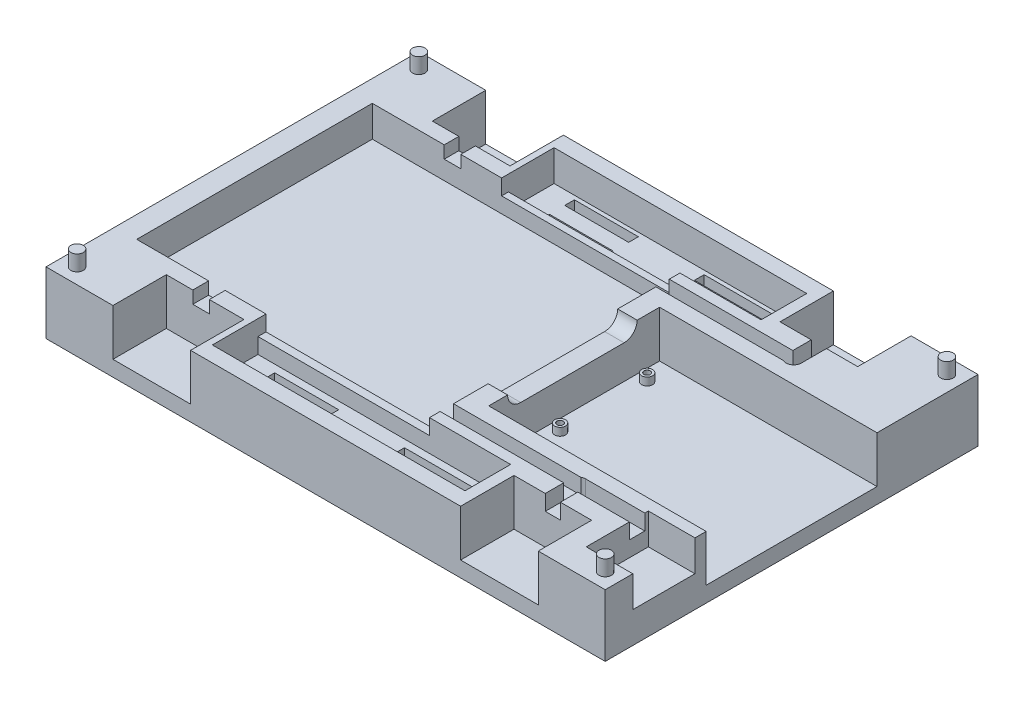
SolidWorks part; units mm, degrees
ref_plane "Front Plane" through (0, 0, 0) normal (0, 0, 1) x (1, 0, 0)
ref_plane "Top Plane" through (0, 0, 0) normal (0, 1, 0) x (1, 0, 0)
ref_plane "Right Plane" through (0, 0, 0) normal (1, 0, 0) x (0, 0, -1)
sketch "Sketch1" plane through (0, 0, 0) normal (0, 1, 0) x (1, 0, 0)
  line L1 (90, 60) -> (-90, 60)
  line L2 (90, 60) -> (90, -60)
  line L3 (90, -60) -> (-90, -60)
  line L4 (-90, 60) -> (-90, -60)
  line L5 (90, 60) -> (-90, -60) construction
  line L6 (90, -60) -> (-90, 60) construction
  point P0 (0, 0)
  dimension "D1" = 180
  dimension "D2" = 120
extrude "Boss-Extrude1" add sketch "Sketch1" along normal blind 20
sketch "Sketch2" plane through (0, 20, 0) normal (0, 1, 0) x (1, 0, 0)
  line L0 (90, 0) -> (90, 27.5)
  line L1 (90, -60) -> (90, 60) construction
  line L2 (90, 0) -> (90, -27.5)
  line L3 (90, 27.5) -> (20, 27.5)
  line L4 (20, 27.5) -> (20, -27.5)
  line L5 (20, -27.5) -> (90, -27.5)
  dimension "D1" = 27.5
  dimension "D2" = 27.5
  dimension "D3" = 70
extrude "Cut-Extrude1" cut sketch "Sketch2" against normal blind 15
sketch "Sketch3" plane through (0, 20, 0) normal (0, 1, 0) x (1, 0, 0)
  line L0 (-90, -60) -> (90, -60) construction
  line L1 (68.4559, -77.185) -> (43.4559, -77.185)
  line L2 (68.4559, -77.185) -> (68.4559, -42.815)
  line L3 (68.4559, -42.815) -> (43.4559, -42.815)
  line L4 (43.4559, -77.185) -> (43.4559, -42.815)
  line L5 (68.4559, -77.185) -> (43.4559, -42.815) construction
  line L6 (68.4559, -42.815) -> (43.4559, -77.185) construction
  point P0 (55.9559, -60)
  dimension "D1" = 25
  dimension "D2" = 34.37
extrude "Cut-Extrude2" cut sketch "Sketch3" against normal blind 15
mirror "Mirror1" about plane through (0, 0, 0) normal (1, 0, 0) of "Cut-Extrude2"
mirror "Mirror2" about plane through (0, 0, 0) normal (0, 0, 1) of "Mirror1", "Cut-Extrude2"
sketch "Sketch4" plane through (0, 20, 0) normal (0, 1, 0) x (1, 0, 0)
  line L1 (-83.0687, 38.109) -> (13.7398, 38.109)
  line L2 (-83.0687, 38.109) -> (-83.0687, -37.7325)
  line L3 (-83.0687, -37.7325) -> (13.7398, -37.7325)
  line L4 (13.7398, 38.109) -> (13.7398, -37.7325)
  dimension "D1" = 75.8415
  dimension "D2" = 96.8085
extrude "Cut-Extrude4" cut sketch "Sketch4" against normal blind 10
sketch "Sketch6" plane through (0, 5, 0) normal (0, 1, 0) x (1, 0, 0)
  line L0 (-62.6949, -357.8384) -> (-777.3616, -357.8384) construction
  circle A0 centre (23.7402, 19.7599) radius 1.7503
  circle A1 centre (23.7402, -8.258) radius 1.75
  circle A3 centre (74.9588, -23.6924) radius 1.75
  dimension "D1" = 3.5
  dimension "D2" = 3.5007
  dimension "D4" = 3.5
extrude "Boss-Extrude2" add sketch "Sketch6" along normal blind 2.5
hole_wizard "Ø2.0 (2) Diameter Hole1" positions "3DSketch7" profile "Sketch12" hole size "Ø2.0" standard "AS"
sketch3d "3DSketch7"
  line L0 (23.7402, 7.5, -19.7599) -> (23.7402, 5, -19.7599) construction
  line L1 (23.7402, 7.5, 8.258) -> (23.7402, 5, 8.258) construction
  line L2 (74.9588, 7.5, 23.6924) -> (74.9588, 5, 23.6924) construction
  point P0 (23.7402, 7.5, -19.7599)
  point P4 (23.7402, 7.5, 8.258)
  point P8 (74.9588, 7.5, 23.6924)
sketch "Sketch12" plane through (23.7402, 7.5, -19.7599) normal (1, 0, 0) x (0, 0, 1)
  line L0 (0, 0) -> (0, 2.6009)
  line L1 (0, 2.6009) -> (1, 2)
  line L2 (1, 2) -> (1, 0.0241)
  line L3 (1, 0.0241) -> (1.025, 0)
  line L5 (1.025, 0) -> (0, 0)
  line L6 (-1, 0.0241) -> (-1.025, 0) construction
  line L10 (0, 2.6009) -> (-1, 2) construction
  line L11 (0, -6.35) -> (0, 107.95) construction
  dimension "Hole Dia." = 2
  dimension "Hole Depth" = 2
  dimension "Near C'Sink Dia." = 2.05
  dimension "Near C'Sink Angle" = 92
  dimension "Drill Angle" = 118
sketch "Sketch14" plane through (0, 20, 0) normal (0, 1, 0) x (1, 0, 0)
  line L0 (-90, 60) -> (-90, 55)
  line L1 (-90, 60) -> (-90, -60) construction
  line L2 (-90, 55) -> (-85, 55)
  line L3 (90, 60) -> (90, 55)
  line L4 (90, 27.5) -> (90, 60) construction
  line L5 (90, 55) -> (85, 55)
  line L6 (-90, -60) -> (-90, -55)
  line L7 (-90, -55) -> (-85, -55)
  line L8 (90, -60) -> (90, -55)
  line L9 (90, -60) -> (90, -27.5) construction
  line L10 (90, -55) -> (85, -55)
  dimension "D1" = 5
  dimension "D2" = 5
  dimension "D3" = 5
  dimension "D4" = 5
  dimension "D5" = 5
  dimension "D6" = 5
  dimension "D7" = 5
  dimension "D8" = 5
sketch "Sketch19" plane through (20, 0, 0) normal (1, 0, 0) x (0, 0, -1)
  line L0 (-17.2052, 20) -> (16.0767, 20) construction
  line L1 (27.5, 20) -> (-27.5, 20) construction
  line L2 (-17.2052, 24.2066) -> (16.0767, 24.2066)
  line L3 (-17.2052, 15.7934) -> (16.0767, 15.7934)
  arc A0 (-17.2052, 24.2066) -> (-17.2052, 15.7934) centre (-17.2052, 20) ccw
  arc A1 (16.0767, 15.7934) -> (16.0767, 24.2066) centre (16.0767, 20) ccw
  point P4 (-0.5642, 20)
extrude "Cut-Extrude5" cut sketch "Sketch19" against normal blind 10
sketch "Sketch21" plane through (0, 0, 60) normal (0, 0, 1) x (1, 0, 0)
  line L0 (-43.4559, 20) -> (43.4559, 20) construction
  line L1 (-4.863, 20) -> (-16.863, 20)
  line L2 (-4.863, 20) -> (-4.863, 14)
  line L3 (-4.863, 14) -> (-16.863, 14)
  line L4 (-16.863, 20) -> (-16.863, 14)
  dimension "D1" = 6
  dimension "D2" = 12
sketch "Sketch22" plane through (0, 0, 37.7325) normal (0, 0, -1) x (-1, 0, 0)
  line L0 (83.0687, 20) -> (-13.7398, 20) construction
  line L1 (12.735, 20) -> (8.1365, 20)
  line L2 (12.735, 20) -> (12.735, 18.4462)
  line L3 (12.735, 18.4462) -> (8.1365, 18.4462)
  line L4 (8.1365, 20) -> (8.1365, 18.4462)
sketch "Sketch23" plane through (0, 20, 0) normal (0, 1, 0) x (1, 0, 0)
  circle A0 centre (-85, 55) radius 2
  circle A1 centre (-85, -55) radius 2
  dimension "D1" = 4
  dimension "D2" = 4
extrude "Boss-Extrude3" add sketch "Sketch23" along normal blind 5
mirror "Mirror3" about plane through (0, 0, 0) normal (1, 0, 0) of "Boss-Extrude3"
sketch "Sketch25" plane through (0, 20, 0) normal (0, 1, 0) x (1, 0, 0)
  line L0 (-68.4559, -42.815) -> (-43.4559, -42.815) construction
  line L1 (-59.9289, -42.815) -> (-54.6037, -42.815)
  line L2 (-59.9289, -42.815) -> (-59.9289, -37.7325)
  line L3 (-59.9289, -37.7325) -> (-54.6037, -37.7325)
  line L4 (-54.6037, -42.815) -> (-54.6037, -37.7325)
  line L5 (-83.0687, -37.7325) -> (13.7398, -37.7325) construction
  line L6 (13.7398, 38.109) -> (-83.0687, 38.109) construction
  line L7 (-59.9289, 38.109) -> (-54.6037, 38.109)
  line L8 (-59.9289, 38.109) -> (-59.9289, 42.815)
  line L9 (-59.9289, 42.815) -> (-54.6037, 42.815)
  line L10 (-54.6037, 38.109) -> (-54.6037, 42.815)
  line L11 (-68.4559, 42.815) -> (-43.4559, 42.815) construction
extrude "Cut-Extrude10" cut sketch "Sketch25" against normal blind 4
sketch "Sketch27" plane through (0, 20, 0) normal (0, 1, 0) x (1, 0, 0)
  line L0 (55.9559, -42.815) -> (55.9559, -34.7253) construction
  line L1 (68.4559, -42.815) -> (43.4559, -42.815) construction
  line L2 (53.5189, -42.815) -> (53.5189, -34.7253)
  line L3 (58.3929, -42.815) -> (58.3929, -34.7253)
  line L4 (55.9559, -34.7253) -> (13.7398, -34.7253) construction
  line L5 (13.7398, -37.7325) -> (13.7398, -21.4118) construction
  line L6 (55.9559, -36.8759) -> (13.7398, -36.8759)
  line L7 (55.9559, -32.5746) -> (13.7398, -32.5746)
  arc A0 (53.5189, -42.815) -> (58.3929, -42.815) centre (55.9559, -42.815) ccw
  arc A1 (58.3929, -34.7253) -> (53.5189, -34.7253) centre (55.9559, -34.7253) ccw
  arc A2 (55.9559, -36.8759) -> (55.9559, -32.5746) centre (55.9559, -34.7253) ccw
  arc A3 (13.7398, -32.5746) -> (13.7398, -36.8759) centre (13.7398, -34.7253) ccw
  point P4 (55.9559, -38.7701)
  point P9 (34.8478, -34.7253)
extrude "Cut-Extrude11" cut sketch "Sketch27" against normal blind 5 contours L3 A1 L2 A0 | L7 A3 L6 A2
mirror "Mirror4" about plane through (0, 0, 0) normal (0, 0, 1) of "Cut-Extrude11"
sketch "Sketch28" plane through (0, 20, 0) normal (0, 1, 0) x (1, 0, 0)
  line L0 (-43.4559, 60) -> (-41.4559, 60)
  line L1 (43.4559, 60) -> (-43.4559, 60) construction
  line L2 (-41.4559, 60) -> (-41.4559, 55)
  line L4 (-41.4559, 55) -> (39.8608, 55)
  line L5 (-41.4559, 55) -> (-41.4559, 40.3083)
  line L6 (-41.4559, 40.3083) -> (39.8608, 40.3083)
  line L7 (39.8608, 55) -> (39.8608, 40.3083)
  dimension "D1" = 2
  dimension "D2" = 5
extrude "Cut-Extrude12" cut sketch "Sketch28" against normal blind 10 contours L7 L4 L5 L6
sketch "Sketch29" plane through (0, 20, 0) normal (0, 1, 0) x (1, 0, 0)
  line L1 (-41.4559, 40.3083) -> (13.7398, 40.3083)
  line L2 (-41.4559, 40.3083) -> (-41.4559, 38.109)
  line L3 (-41.4559, 38.109) -> (13.7398, 38.109)
  line L4 (13.7398, 40.3083) -> (13.7398, 38.109)
extrude "Cut-Extrude13" cut sketch "Sketch29" against normal blind 5
sketch "Sketch30" plane through (0, 10, 0) normal (0, 1, 0) x (1, 0, 0)
  line L1 (31.2803, 53.7352) -> (8.1082, 53.7352)
  line L2 (31.2803, 53.7352) -> (31.2803, 50.6038)
  line L3 (31.2803, 50.6038) -> (8.1082, 50.6038)
  line L4 (8.1082, 53.7352) -> (8.1082, 50.6038)
  line L5 (8.1082, 45.6831) -> (31.2803, 45.6831)
  line L6 (8.1082, 45.6831) -> (8.1082, 42.7307)
  line L7 (8.1082, 42.7307) -> (31.2803, 42.7307)
  line L8 (31.2803, 45.6831) -> (31.2803, 42.7307)
  line L9 (-13.0612, 50.6038) -> (-33.6478, 50.6038)
  line L10 (-13.0612, 50.6038) -> (-13.0612, 53.7352)
  line L11 (-13.0612, 53.7352) -> (-33.6478, 53.7352)
  line L12 (-33.6478, 50.6038) -> (-33.6478, 53.7352)
  line L13 (-33.6478, 45.6831) -> (-13.0612, 45.6831)
  line L14 (-33.6478, 45.6831) -> (-33.6478, 42.7307)
  line L15 (-33.6478, 42.7307) -> (-13.0612, 42.7307)
  line L16 (-13.0612, 45.6831) -> (-13.0612, 42.7307)
extrude "Cut-Extrude15" cut sketch "Sketch30" against normal through all
mirror "Mirror5" about plane through (0, 0, 0) normal (0, 0, 1) of "Cut-Extrude12", "Cut-Extrude13", "Cut-Extrude15"
sketch "Sketch31" plane through (0, 20, 0) normal (0, 1, 0) x (1, 0, 0)
  line L1 (-41.4559, -38.109) -> (13.7398, -38.109)
  line L2 (-41.4559, -38.109) -> (-41.4559, -37.7325)
  line L3 (-41.4559, -37.7325) -> (13.7398, -37.7325)
  line L4 (13.7398, -38.109) -> (13.7398, -37.7325)
extrude "Cut-Extrude16" cut sketch "Sketch31" against normal blind 5
sketch "Sketch32" plane through (90, 0, 0) normal (1, 0, 0) x (0, 0, -1)
  line L0 (-60, 20) -> (-27.5, 20) construction
  line L1 (-31.109, 20) -> (-51.109, 20)
  line L2 (-31.109, 20) -> (-31.109, 10)
  line L3 (-31.109, 10) -> (-51.109, 10)
  line L4 (-51.109, 20) -> (-51.109, 10)
  dimension "D1" = 20
  dimension "D2" = 10
extrude "Cut-Extrude17" cut sketch "Sketch32" against normal blind 15
sketch "Sketch33" plane through (0, 20, 0) normal (0, 1, 0) x (1, 0, 0)
  line L0 (55.9559, -34.7253) -> (75, -34.7253) construction
  line L1 (75, -31.109) -> (75, -51.109) construction
  line L2 (55.9559, -32.2534) -> (75, -32.2534)
  line L3 (55.9559, -37.1971) -> (75, -37.1971)
  arc A0 (55.9559, -32.2534) -> (55.9559, -37.1971) centre (55.9559, -34.7253) ccw
  arc A1 (75, -37.1971) -> (75, -32.2534) centre (75, -34.7253) ccw
  point P5 (65.4779, -34.7253)
extrude "Cut-Extrude18" cut sketch "Sketch33" against normal blind 5
